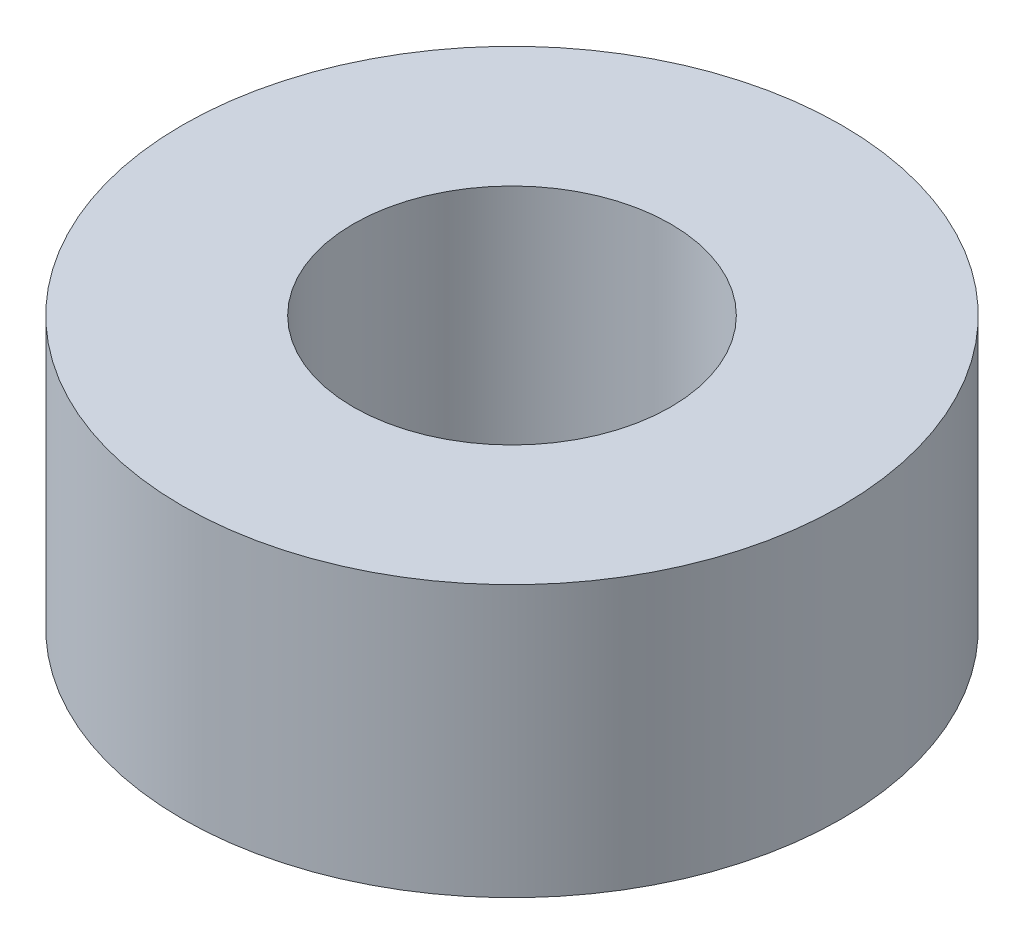
SolidWorks part; units mm, degrees
ref_plane "Front Plane" through (0, 0, 0) normal (0, 0, 1) x (1, 0, 0)
ref_plane "Top Plane" through (0, 0, 0) normal (0, 1, 0) x (1, 0, 0)
ref_plane "Right Plane" through (0, 0, 0) normal (1, 0, 0) x (0, 0, -1)
sketch "Sketch1" plane through (0, 0, 0) normal (0, 1, 0) x (1, 0, 0)
  circle A0 centre (0, 0) radius 2.75
  circle A1 centre (0, 0) radius 5.715
  dimension "D1" = 5.5
  dimension "D2" = 11.43
extrude "Boss-Extrude1" add sketch "Sketch1" along normal blind 4.699
